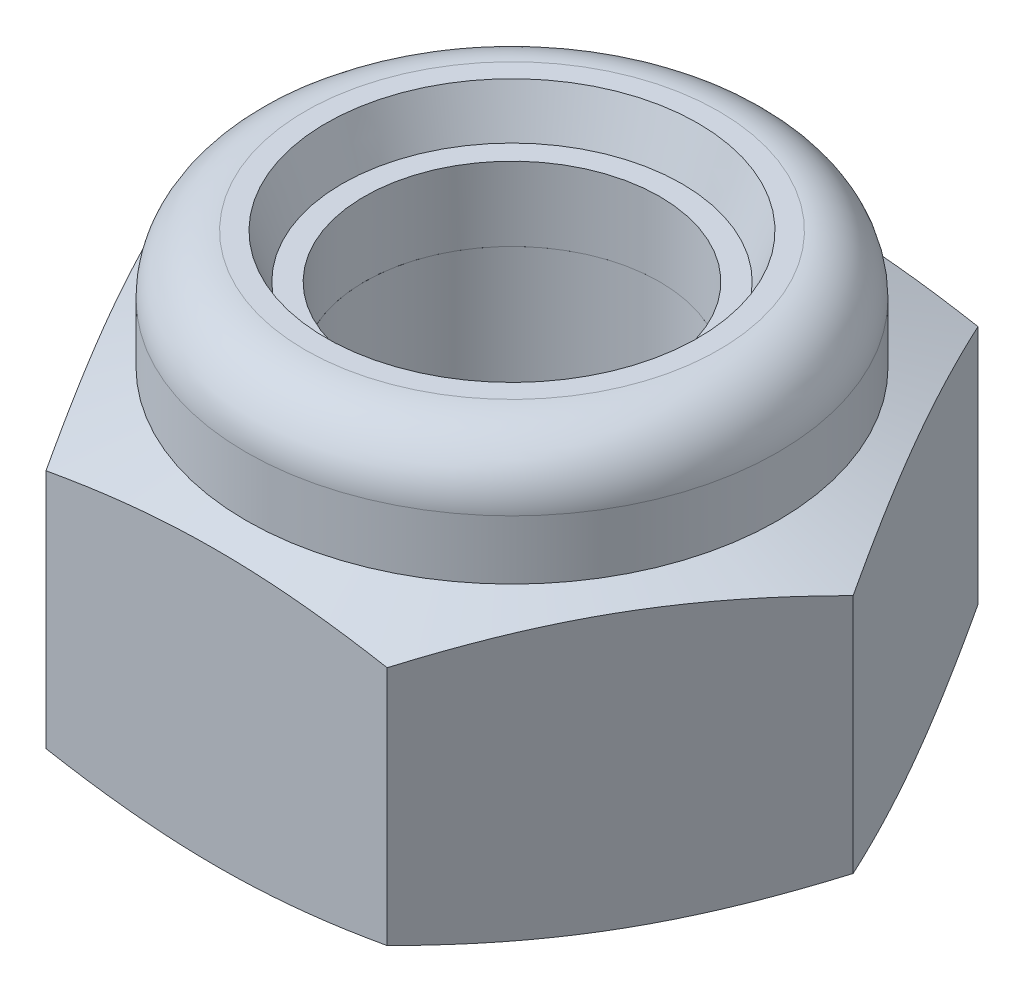
SolidWorks part; units mm, degrees
material "AISI 304"
ref_plane "前视基准面" through (0, 0, 0) normal (0, 0, 1) x (1, 0, 0)
ref_plane "上视基准面" through (0, 0, 0) normal (0, 1, 0) x (1, 0, 0)
ref_plane "右视基准面" through (0, 0, 0) normal (1, 0, 0) x (0, 0, -1)
other "Configuration Table"
sketch "草图1" plane through (0, 0, 0) normal (0, 0, 1) x (1, 0, 0)
  line L0 (0, -0.0416) -> (0, 2990.141) construction
  line L1 (1, 2) -> (1, 0.1732)
  line L2 (1, 0.1732) -> (1.3, 0)
  line L3 (1.3, 0) -> (1.8, 0)
  line L4 (1.8, 0) -> (1.8, 2.4)
  line L5 (1.4, 2.8) -> (1.2592, 2.8)
  line L6 (1.2592, 2.8) -> (1.15, 2.5)
  line L8 (1, 2) -> (1.3, 2)
  line L9 (1.3, 2) -> (1.3, 2.5)
  line L10 (1.3, 2.5) -> (1.15, 2.5)
  arc A0 (1.8, 2.4) -> (1.4, 2.8) centre (1.4, 2.4) ccw
  point P18 (1.15, 2)
  dimension "a" = 0.4
  dimension "D" = 2
  dimension "dw" = 3.6
  dimension "m" = 2
  dimension "da" = 2.6
  dimension "theta" = 60
  dimension "h" = 2.8
  dimension "t" = 0.5
  dimension "hj" = 0.3
  dimension "D10" = 70
revolve "旋转1" add sketch "草图1" angle 360 about L0
sketch "草图2" plane through (0, 0, 0) normal (0, 1, 0) x (1, 0, 0)
  line L1 (2.3094, 0) -> (1.1547, 2)
  line L2 (1.1547, 2) -> (-1.1547, 2)
  line L3 (-1.1547, 2) -> (-2.3094, 0)
  line L4 (-2.3094, 0) -> (-1.1547, -2)
  line L5 (-1.1547, -2) -> (1.1547, -2)
  line L6 (1.1547, -2) -> (2.3094, 0)
  circle A0 centre (0, 0) radius 1.8 construction
  circle A1 centre (0, 0) radius 1.8 construction
  circle A2 centre (0, 0) radius 1.3
  circle A3 centre (0, 0) radius 1.3 construction
  dimension "s" = 4
extrude "凸台-拉伸1" add sketch "草图2" along normal blind 2
sketch "草图3" plane through (0, 0, 0) normal (0, 0, 1) x (1, 0, 0)
  line L0 (-1.8, 2) -> (-2.3094, 1.8146)
  line L1 (-2.3094, 2) -> (-2.3094, 0) construction
  line L2 (-2.3094, 1.8146) -> (-2.3094, 2)
  line L3 (-2.3094, 2) -> (-1.8, 2)
  line L4 (-1.8, 0) -> (-2.3094, 0)
  line L5 (-2.3094, 0) -> (-1.1547, 0) construction
  line L6 (-2.3094, 0) -> (-2.3094, 0.1854)
  line L7 (-2.3094, 0.1854) -> (-1.8, 0)
  line L8 (0, 0) -> (0, 50000) construction
  dimension "D1" = 20
revolve "切除-旋转1" cut sketch "草图3" angle 360 about L8
sketch "草图4" plane through (0, 2, 0) normal (0, 1, 0) x (1, 0, 0)
  circle A0 centre (0, 0) radius 1
  circle A1 centre (0, 0) radius 1.3
  circle A2 centre (0, 0) radius 1.3 construction
  circle A3 centre (0, 0) radius 1 construction
extrude "凸台-拉伸2" add sketch "草图4" along normal up to surface (0.5 mm away) separate body up to face at (0, 2.5, -1.3)
